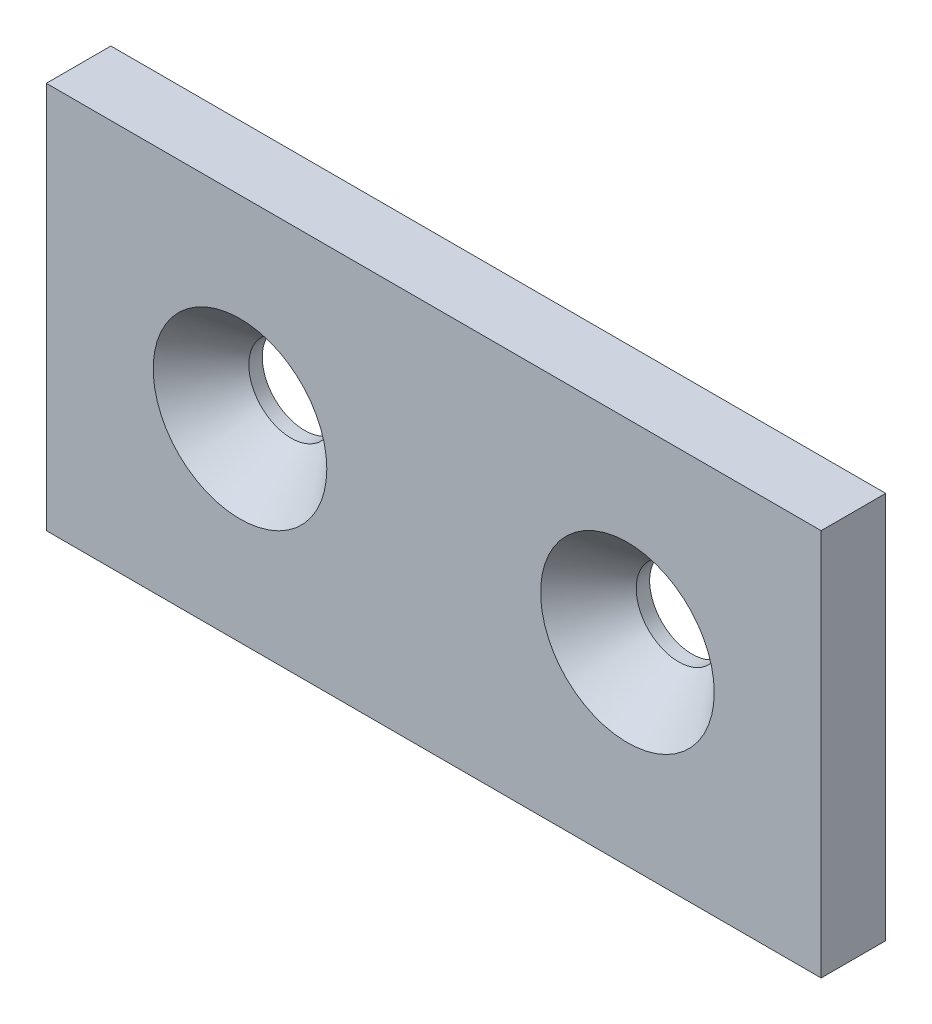
SolidWorks part; units mm, degrees
ref_plane "Front Plane" through (0, 0, 0) normal (0, 0, 1) x (1, 0, 0)
ref_plane "Top Plane" through (0, 0, 0) normal (0, 1, 0) x (1, 0, 0)
ref_plane "Right Plane" through (0, 0, 0) normal (1, 0, 0) x (0, 0, -1)
sketch "Sketch1" plane through (0, 0, 0) normal (0, 0, 1) x (1, 0, 0)
  line L0 (0, 0) -> (0, 38.1)
  line L1 (19.05, 19.05) -> (57.15, 19.05) construction
  line L4 (76.2, 38.1) -> (0, 38.1)
  line L5 (76.2, 0) -> (0, 0)
  line L7 (76.2, 38.1) -> (76.2, 0)
  circle A0 centre (19.05, 19.05) radius 4.1656
  circle A1 centre (57.15, 19.05) radius 4.1656
  dimension "D1" = 38.1
  dimension "E" = 8.3312
  dimension "D2" = 19.05
  dimension "C" = 38.1
  dimension "D3" = 19.05
  dimension "B" = 76.2
extrude "Boss-Extrude1" add sketch "Sketch1" along normal mid plane 6.35
sketch "Sketch2" plane through (0, 0, 3.175) normal (0, 0, 1) x (1, 0, 0)
  circle A0 centre (19.05, 19.05) radius 4.1656 construction
  circle A1 centre (19.05, 19.05) radius 4.1656
  circle A2 centre (57.15, 19.05) radius 4.1656 construction
  circle A3 centre (57.15, 19.05) radius 4.1656
extrude "Cut-Extrude1" cut sketch "Sketch2" along normal through all draft 41 from offset 5.0292 offset against normal yes draft outward yes
